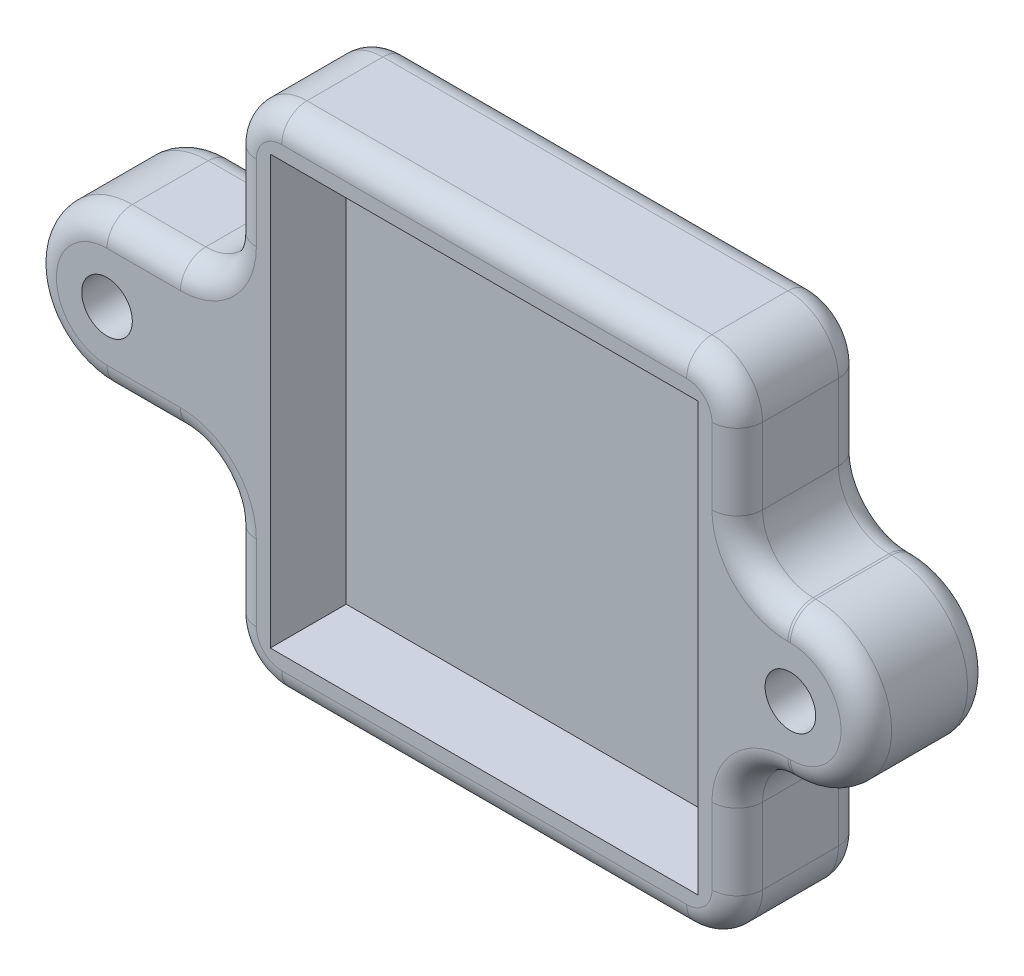
SolidWorks part; units mm, degrees
ref_plane "Front Plane" through (0, 0, 0) normal (0, 0, 1) x (1, 0, 0)
ref_plane "Top Plane" through (0, 0, 0) normal (0, 1, 0) x (1, 0, 0)
ref_plane "Right Plane" through (0, 0, 0) normal (1, 0, 0) x (0, 0, -1)
sketch "Sketch1" plane through (0, 0, 0) normal (0, 0, 1) x (1, 0, 0)
  line L0 (0, 10) -> (0, -10) construction
  line L1 (-5.1, 8) -> (10.9, 8) construction
  line L2 (-5.1, 8) -> (-5.1, -8) construction
  line L3 (-5.1, -8) -> (10.9, -8) construction
  line L4 (10.9, 8) -> (10.9, -8) construction
  line L5 (-12, 0) -> (15, 0) construction
  line L6 (-12, 3) -> (-7.1, 3)
  line L7 (-7.1, 10) -> (12.9, 10)
  line L8 (-7.1, 10) -> (-7.1, 3)
  line L9 (-7.1, -10) -> (12.9, -10)
  line L10 (12.9, 10) -> (12.9, 3)
  line L11 (-12, -3) -> (-7.1, -3)
  line L12 (15, -3) -> (12.9, -3)
  line L13 (15, 3) -> (12.9, 3)
  line L14 (-7.1, -3) -> (-7.1, -10)
  line L15 (12.9, -3) -> (12.9, -10)
  circle A0 centre (-12, 0) radius 1
  circle A1 centre (15, 0) radius 1
  arc A2 (-12, 3) -> (-12, -3) centre (-12, 0) ccw
  arc A3 (15, -3) -> (15, 3) centre (15, 0) ccw
  circle A4 centre (0, 0) radius 1 construction
  point P0 (0, 0)
  point P6 (0, 0)
  dimension "D5" = 2
  dimension "D6" = 12
  dimension "D8" = 2
  dimension "D10" = 6
  dimension "D1" = 16
  dimension "D2" = 2
  dimension "D3" = 2
  dimension "D4" = 2
  dimension "D7" = 5.1
  dimension "D9" = 15
extrude "Boss-Extrude1" add sketch "Sketch1" along normal blind 5
sketch "Sketch2" plane through (0, 0, 5) normal (0, 0, 1) x (1, 0, 0)
  line L0 (-5.1, -8) -> (10.9, -8) construction
  line L1 (10.9, 8) -> (10.9, -8) construction
  line L2 (-5.1, 8) -> (10.9, 8) construction
  line L3 (-5.1, 8) -> (-5.1, -8) construction
  line L4 (-5.1, -8) -> (10.9, -8) construction
  line L5 (10.9, 8) -> (10.9, -8) construction
  line L6 (-5.1, 8) -> (10.9, 8) construction
  line L7 (-5.1, 8) -> (-5.1, -8) construction
  line L9 (-5.55, 8.45) -> (11.35, 8.45)
  line L10 (-5.55, 8.45) -> (-5.55, -8.45)
  line L11 (-5.55, -8.45) -> (11.35, -8.45)
  line L12 (11.35, 8.45) -> (11.35, -8.45)
  dimension "D1" = 0.45
  dimension "D2" = 0.45
  dimension "D3" = 0.45
  dimension "D4" = 0.45
extrude "Cut-Extrude1" cut sketch "Sketch2" against normal blind 3
fillet "Fillet1" radius 2 8 edges at (12.9, -10, 2.5) (-7.1, -10, 2.5) (-7.1, -3, 2.5) (-7.1, 3, 2.5) (-7.1, 10, 2.5) (12.9, 10, 2.5) (12.9, 3, 2.5) (12.9, -3, 2.5)
fillet "Fillet2" radius 1 40 edges at (-6.5142, -9.4142, 5) (-7.1, -6.5, 5) (-7.6858, -3.5858, 5) (-15, 0, 5) (-7.6858, 3.5858, 5) (-7.1, 6.5, 5) (-6.5142, 9.4142, 5) (2.9, 10, 5) (12.3142, 9.4142, 5) (12.9, 6.5, 5) (13.4858, 3.5858, 5) (14.95, 3, 5) (18, 0, 5) (14.95, -3, 5) (13.4858, -3.5858, 5) (12.9, -6.5, 5) (12.3142, -9.4142, 5) (-6.5142, -9.4142, 0) (-7.1, -6.5, 0) (-7.6858, -3.5858, 0) (-15, 0, 0) (-7.6858, 3.5858, 0) (-7.1, 6.5, 0) (-6.5142, 9.4142, 0) (2.9, 10, 0) (12.3142, 9.4142, 0) (12.9, 6.5, 0) (13.4858, 3.5858, 0) (14.95, 3, 0) (18, 0, 0) (14.95, -3, 0) (13.4858, -3.5858, 0) (12.9, -6.5, 0) (12.3142, -9.4142, 0) (2.9, -10, 5) (2.9, -10, 0) (-10.55, -3, 5) (-10.55, 3, 5) (-10.55, -3, 0) (-10.55, 3, 0)
